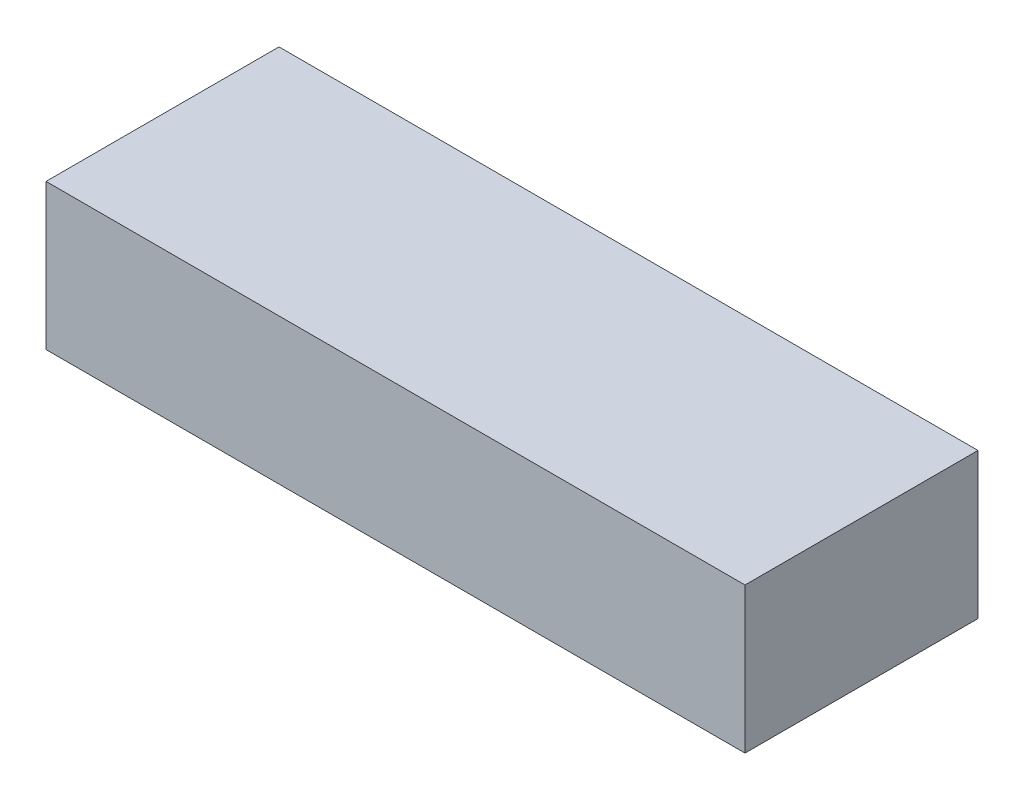
SolidWorks part; units mm, degrees
ref_plane "前视基准面" through (0, 0, 0) normal (0, 0, 1) x (1, 0, 0)
ref_plane "上视基准面" through (0, 0, 0) normal (0, 1, 0) x (1, 0, 0)
ref_plane "右视基准面" through (0, 0, 0) normal (1, 0, 0) x (0, 0, -1)
sketch "Sketch1" plane through (0, 0, 0) normal (0, 1, 0) x (1, 0, 0)
  line L1 (-60, -20) -> (60, -20)
  line L2 (-60, -20) -> (-60, 20)
  line L3 (-60, 20) -> (60, 20)
  line L4 (60, -20) -> (60, 20)
  line L5 (-60, -20) -> (60, 20) construction
  line L6 (-60, 20) -> (60, -20) construction
  point P0 (0, 0)
extrude "Extrude1" add sketch "Sketch1" along normal blind 25
